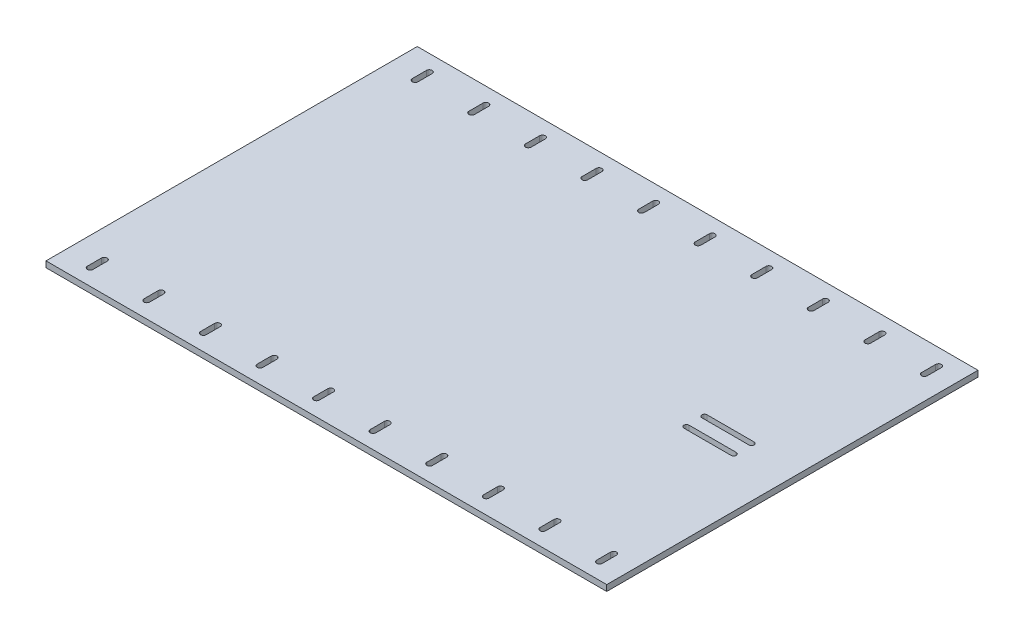
SolidWorks part; units mm, degrees
ref_plane "Front Plane" through (0, 0, 0) normal (0, 0, 1) x (1, 0, 0)
ref_plane "Top Plane" through (0, 0, 0) normal (0, 1, 0) x (1, 0, 0)
ref_plane "Right Plane" through (0, 0, 0) normal (1, 0, 0) x (0, 0, -1)
sketch "Sketch1" plane through (0, 0, 0) normal (0, 1, 0) x (1, 0, 0)
  line L0 (0, 369.15) -> (609.6, 369.15) construction
  line L1 (0, 0) -> (609.6, 0)
  line L2 (0, 0) -> (0, 393.7)
  line L3 (0, 393.7) -> (609.6, 393.7)
  line L4 (609.6, 0) -> (609.6, 393.7)
  line L5 (0, 24.55) -> (609.6, 24.55) construction
  line L6 (584.8, 32.05) -> (584.8, 17.05) construction
  line L9 (587.8, 32.05) -> (587.8, 17.05)
  line L10 (581.8, 32.05) -> (581.8, 17.05)
  line L11 (524.8, 32.05) -> (524.8, 17.05) construction
  line L12 (527.8, 32.05) -> (527.8, 17.05)
  line L13 (521.8, 32.05) -> (521.8, 17.05)
  line L14 (464.8, 32.05) -> (464.8, 17.05) construction
  line L15 (467.8, 32.05) -> (467.8, 17.05)
  line L16 (461.8, 32.05) -> (461.8, 17.05)
  line L17 (404.8, 32.05) -> (404.8, 17.05) construction
  line L18 (407.8, 32.05) -> (407.8, 17.05)
  line L19 (401.8, 32.05) -> (401.8, 17.05)
  line L20 (344.8, 32.05) -> (344.8, 17.05) construction
  line L21 (347.8, 32.05) -> (347.8, 17.05)
  line L22 (341.8, 32.05) -> (341.8, 17.05)
  line L23 (284.8, 32.05) -> (284.8, 17.05) construction
  line L24 (287.8, 32.05) -> (287.8, 17.05)
  line L25 (281.8, 32.05) -> (281.8, 17.05)
  line L26 (224.8, 32.05) -> (224.8, 17.05) construction
  line L27 (227.8, 32.05) -> (227.8, 17.05)
  line L28 (221.8, 32.05) -> (221.8, 17.05)
  line L29 (164.8, 32.05) -> (164.8, 17.05) construction
  line L30 (167.8, 32.05) -> (167.8, 17.05)
  line L31 (161.8, 32.05) -> (161.8, 17.05)
  line L32 (104.8, 32.05) -> (104.8, 17.05) construction
  line L33 (107.8, 32.05) -> (107.8, 17.05)
  line L34 (101.8, 32.05) -> (101.8, 17.05)
  line L35 (44.8, 32.05) -> (44.8, 17.05) construction
  line L36 (47.8, 32.05) -> (47.8, 17.05)
  line L37 (41.8, 32.05) -> (41.8, 17.05)
  line L38 (524.8, 376.65) -> (524.8, 361.65) construction
  line L39 (527.8, 376.65) -> (527.8, 361.65)
  line L40 (521.8, 376.65) -> (521.8, 361.65)
  line L41 (464.8, 376.65) -> (464.8, 361.65) construction
  line L42 (467.8, 376.65) -> (467.8, 361.65)
  line L43 (461.8, 376.65) -> (461.8, 361.65)
  line L44 (404.8, 376.65) -> (404.8, 361.65) construction
  line L45 (407.8, 376.65) -> (407.8, 361.65)
  line L46 (401.8, 376.65) -> (401.8, 361.65)
  line L47 (344.8, 376.65) -> (344.8, 361.65) construction
  line L48 (347.8, 376.65) -> (347.8, 361.65)
  line L49 (341.8, 376.65) -> (341.8, 361.65)
  line L50 (284.8, 376.65) -> (284.8, 361.65) construction
  line L51 (287.8, 376.65) -> (287.8, 361.65)
  line L52 (281.8, 376.65) -> (281.8, 361.65)
  line L53 (224.8, 376.65) -> (224.8, 361.65) construction
  line L54 (227.8, 376.65) -> (227.8, 361.65)
  line L55 (221.8, 376.65) -> (221.8, 361.65)
  line L56 (164.8, 376.65) -> (164.8, 361.65) construction
  line L57 (167.8, 376.65) -> (167.8, 361.65)
  line L58 (161.8, 376.65) -> (161.8, 361.65)
  line L59 (104.8, 376.65) -> (104.8, 361.65) construction
  line L60 (107.8, 376.65) -> (107.8, 361.65)
  line L61 (101.8, 376.65) -> (101.8, 361.65)
  line L62 (44.8, 376.65) -> (44.8, 361.65) construction
  line L63 (47.8, 376.65) -> (47.8, 361.65)
  line L64 (41.8, 376.65) -> (41.8, 361.65)
  line L65 (584.8, 376.65) -> (584.8, 361.65) construction
  line L66 (587.8, 376.65) -> (587.8, 361.65)
  line L67 (581.8, 376.65) -> (581.8, 361.65)
  line L68 (609.6, 187.325) -> (0, 187.325) construction
  line L69 (0, 206.375) -> (609.6, 206.375) construction
  line L70 (506.85, 206.375) -> (556.85, 206.375) construction
  line L71 (506.85, 209.125) -> (556.85, 209.125)
  line L72 (506.85, 203.625) -> (556.85, 203.625)
  line L73 (506.85, 187.325) -> (556.85, 187.325) construction
  line L74 (506.85, 190.075) -> (556.85, 190.075)
  line L75 (506.85, 184.575) -> (556.85, 184.575)
  arc A22 (587.8, 32.05) -> (581.8, 32.05) centre (584.8, 32.05) ccw
  arc A23 (581.8, 17.05) -> (587.8, 17.05) centre (584.8, 17.05) ccw
  arc A24 (506.85, 209.125) -> (506.85, 203.625) centre (506.85, 206.375) ccw
  arc A25 (527.8, 32.05) -> (521.8, 32.05) centre (524.8, 32.05) ccw
  arc A26 (521.8, 17.05) -> (527.8, 17.05) centre (524.8, 17.05) ccw
  arc A27 (467.8, 32.05) -> (461.8, 32.05) centre (464.8, 32.05) ccw
  arc A28 (461.8, 17.05) -> (467.8, 17.05) centre (464.8, 17.05) ccw
  arc A29 (407.8, 32.05) -> (401.8, 32.05) centre (404.8, 32.05) ccw
  arc A30 (401.8, 17.05) -> (407.8, 17.05) centre (404.8, 17.05) ccw
  arc A31 (347.8, 32.05) -> (341.8, 32.05) centre (344.8, 32.05) ccw
  arc A32 (341.8, 17.05) -> (347.8, 17.05) centre (344.8, 17.05) ccw
  arc A33 (287.8, 32.05) -> (281.8, 32.05) centre (284.8, 32.05) ccw
  arc A34 (281.8, 17.05) -> (287.8, 17.05) centre (284.8, 17.05) ccw
  arc A35 (227.8, 32.05) -> (221.8, 32.05) centre (224.8, 32.05) ccw
  arc A36 (221.8, 17.05) -> (227.8, 17.05) centre (224.8, 17.05) ccw
  arc A37 (167.8, 32.05) -> (161.8, 32.05) centre (164.8, 32.05) ccw
  arc A38 (161.8, 17.05) -> (167.8, 17.05) centre (164.8, 17.05) ccw
  arc A39 (107.8, 32.05) -> (101.8, 32.05) centre (104.8, 32.05) ccw
  arc A40 (101.8, 17.05) -> (107.8, 17.05) centre (104.8, 17.05) ccw
  arc A41 (47.8, 32.05) -> (41.8, 32.05) centre (44.8, 32.05) ccw
  arc A42 (41.8, 17.05) -> (47.8, 17.05) centre (44.8, 17.05) ccw
  arc A43 (527.8, 376.65) -> (521.8, 376.65) centre (524.8, 376.65) ccw
  arc A44 (521.8, 361.65) -> (527.8, 361.65) centre (524.8, 361.65) ccw
  arc A45 (467.8, 376.65) -> (461.8, 376.65) centre (464.8, 376.65) ccw
  arc A46 (461.8, 361.65) -> (467.8, 361.65) centre (464.8, 361.65) ccw
  arc A47 (407.8, 376.65) -> (401.8, 376.65) centre (404.8, 376.65) ccw
  arc A48 (401.8, 361.65) -> (407.8, 361.65) centre (404.8, 361.65) ccw
  arc A49 (347.8, 376.65) -> (341.8, 376.65) centre (344.8, 376.65) ccw
  arc A50 (341.8, 361.65) -> (347.8, 361.65) centre (344.8, 361.65) ccw
  arc A51 (287.8, 376.65) -> (281.8, 376.65) centre (284.8, 376.65) ccw
  arc A52 (281.8, 361.65) -> (287.8, 361.65) centre (284.8, 361.65) ccw
  arc A53 (227.8, 376.65) -> (221.8, 376.65) centre (224.8, 376.65) ccw
  arc A54 (221.8, 361.65) -> (227.8, 361.65) centre (224.8, 361.65) ccw
  arc A55 (167.8, 376.65) -> (161.8, 376.65) centre (164.8, 376.65) ccw
  arc A56 (161.8, 361.65) -> (167.8, 361.65) centre (164.8, 361.65) ccw
  arc A57 (107.8, 376.65) -> (101.8, 376.65) centre (104.8, 376.65) ccw
  arc A58 (101.8, 361.65) -> (107.8, 361.65) centre (104.8, 361.65) ccw
  arc A59 (47.8, 376.65) -> (41.8, 376.65) centre (44.8, 376.65) ccw
  arc A60 (41.8, 361.65) -> (47.8, 361.65) centre (44.8, 361.65) ccw
  arc A61 (587.8, 376.65) -> (581.8, 376.65) centre (584.8, 376.65) ccw
  arc A62 (581.8, 361.65) -> (587.8, 361.65) centre (584.8, 361.65) ccw
  arc A63 (556.85, 203.625) -> (556.85, 209.125) centre (556.85, 206.375) ccw
  arc A64 (506.85, 190.075) -> (506.85, 184.575) centre (506.85, 187.325) ccw
  arc A65 (556.85, 184.575) -> (556.85, 190.075) centre (556.85, 187.325) ccw
  point P12 (524.8, 24.55)
  point P19 (464.8, 24.55)
  point P26 (404.8, 24.55)
  point P32 (531.85, 206.375)
  point P38 (531.85, 187.325)
  point P51 (584.8, 24.55)
  point P63 (344.8, 24.55)
  point P70 (284.8, 24.55)
  point P77 (224.8, 24.55)
  point P84 (164.8, 24.55)
  point P91 (104.8, 24.55)
  point P98 (44.8, 24.55)
  point P105 (524.8, 369.15)
  point P112 (464.8, 369.15)
  point P119 (404.8, 369.15)
  point P126 (344.8, 369.15)
  point P133 (284.8, 369.15)
  point P140 (224.8, 369.15)
  point P147 (164.8, 369.15)
  point P154 (104.8, 369.15)
  point P161 (44.8, 369.15)
  point P168 (584.8, 369.15)
  dimension "D5" = 60
  dimension "D12" = 15
  dimension "D15" = 50
  dimension "D1" = 393.7
  dimension "D2" = 609.6
  dimension "D3" = 10
  dimension "D4" = 2
  dimension "D8" = 187.325
  dimension "D9" = 5.5
  dimension "D10" = 24.55
  dimension "D11" = 24.55
  dimension "D13" = 6
  dimension "D14" = 24.8
  dimension "D6" = 344.6
  dimension "D7" = 187.325
  dimension "D16" = 50
extrude "Boss-Extrude1" add sketch "Sketch1" along normal blind 6.35
sketch "Sketch2" plane through (0, 6.35, 0) normal (0, 1, 0) x (1, 0, 0)
  line L0 (0, 0) -> (609.6, 0) construction
  line L1 (0, 393.7) -> (15, 393.7)
  line L2 (0, 393.7) -> (0, 0)
  line L3 (0, 0) -> (15, 0)
  line L4 (15, 393.7) -> (15, 0)
  dimension "D1" = 15
extrude "Cut-Extrude1" cut sketch "Sketch2" against normal up to next
